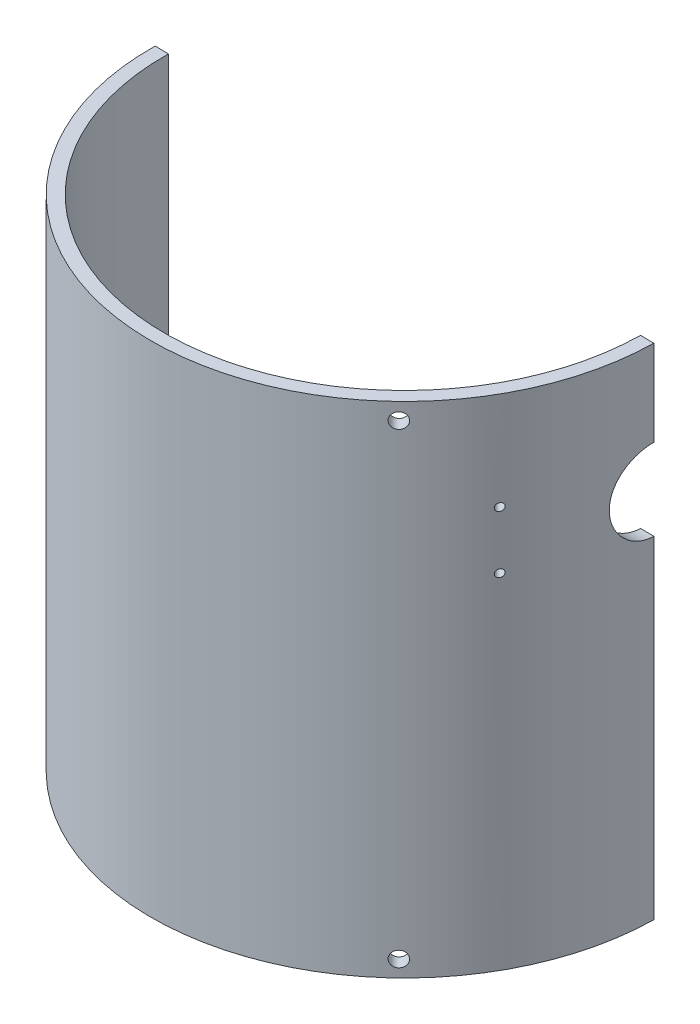
SolidWorks part; units mm, degrees
material "6061 Alloy"
ref_plane "Front Plane" through (0, 0, 0) normal (0, 0, 1) x (1, 0, 0)
ref_plane "Top Plane" through (0, 0, 0) normal (0, 1, 0) x (1, 0, 0)
ref_plane "Right Plane" through (0, 0, 0) normal (1, 0, 0) x (0, 0, -1)
sketch "Sketch1" plane through (0, 0, 0) normal (0, 1, 0) x (0.9999, 0, 0.016)
  line L0 (70.3723, 4.8181) -> (66.8563, 4.8181)
  line L1 (-58.8517, 4.8181) -> (-62.3677, 4.8181)
  arc A1 (-58.8517, 4.8181) -> (66.8563, 4.8181) centre (4.0023, 4.8181) ccw
  arc A3 (-62.3677, 4.8181) -> (70.3723, 4.8181) centre (4.0023, 4.8181) ccw
extrude "Boss-Extrude1" add sketch "Sketch1" along normal blind 130.8
extrude "Cut-Extrude1" cut sketch "Sketch2" along normal blind 129.8
sketch "Sketch2" plane through (-0.8222, 47.8999, 51.5389) normal (-0.016, 0, 0.9999) x (0.9999, 0, 0.016)
  circle A0 centre (4.0023, 7.9001) radius 10.65
  circle A1 centre (4.0426, 7.8539) radius 10.2112
sketch "Sketch9" plane through (0, 0, 0) normal (0, 0, 1) x (1, 0, 0)
  line L0 (68.4244, 130.8) -> (68.4244, 64.9) construction
  point P8 (-56.7516, 64.9)
  point P9 (-14.7819, 64.9)
  point P12 (40.8921, 64.9)
sketch "Sketch10" plane through (0, 0, 0) normal (1, 0, 0) x (0, 0, -1)
  line L2 (-59.6004, 64.9) -> (0, 64.9) construction
ref_plane "Plane1" through (0, 64.9, 0) normal (0, 1, 0) x (-1, 0, 0)
sketch "Sketch19" plane through (0, 130.8, 0) normal (0, 1, 0) x (1, 0, 0)
  circle A0 centre (4.0786, 4.7536) radius 60.838
sketch "Sketch24" plane through (0, 130.8, 0) normal (0, 1, 0) x (1, 0, 0)
  circle A0 centre (4.0786, 4.7536) radius 60.838
extrude "Cut-Extrude2" cut sketch "Sketch34" along normal through all
sketch "Sketch34" plane through (4.4096, 18.5834, -25.4974) normal (0.9999, 0, 0.016) x (0.016, 0, -0.9999)
  circle A0 centre (-20.7464, 79.0666) radius 10.65
extrude "Cut-Extrude3" cut sketch "Sketch35" against normal through all
sketch "Sketch35" plane through (4.4096, 18.5834, -25.4974) normal (0.9999, 0, 0.016) x (0.016, 0, -0.9999)
  circle A0 centre (-20.7464, 30.6666) radius 10.65
extrude "Cut-Extrude8" cut sketch "Sketch40" along normal through all and the other way through all
sketch "Sketch40" plane through (3.6777, 38.8999, -5.1674) normal (0.7182, 0, -0.6958) x (-0.6958, 0, -0.7182)
  line L0 (-0.5762, 87.5501) -> (-0.5762, -34.5999) construction
  circle A0 centre (-0.5762, 87.5501) radius 2
  circle A1 centre (-0.5762, -34.5999) radius 2
extrude "Cut-Extrude9" cut sketch "Sketch41" against normal through all and the other way through all
sketch "Sketch41" plane through (8.5582, 38.8999, -9.0934) normal (-0.6958, 0, -0.7182) x (-0.7182, 0, 0.6958)
  line L0 (6.237, -34.5999) -> (6.237, 87.5501) construction
  circle A0 centre (6.237, 87.5501) radius 2
  circle A1 centre (6.237, -34.5999) radius 2
extrude "Cut-Extrude10" cut sketch "Sketch42" against normal through all
sketch "Sketch42" plane through (57.4749, 38.8999, 41.4094) normal (0.6957, 0, 0.7183) x (0.7183, 0, -0.6957)
  circle A0 centre (12.4095, 66.2501) radius 1
  circle A1 centre (12.4095, 51.2501) radius 1
extrude "Cut-Extrude11" cut sketch "Sketch43" against normal through all
sketch "Sketch43" plane through (-46.825, 38.8999, 43.7483) normal (-0.7183, 0, 0.6957) x (0.6957, 0, 0.7183)
  circle A0 centre (-18.2112, 17.8501) radius 1
  circle A1 centre (-18.2112, 2.8501) radius 1
